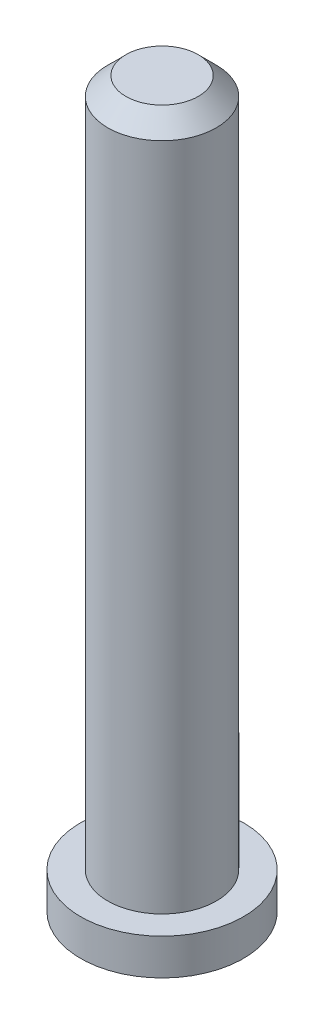
SolidWorks part; units mm, degrees
ref_plane "Спереди" through (0, 0, 0) normal (0, 0, 1) x (1, 0, 0)
ref_plane "Сверху" through (0, 0, 0) normal (0, 1, 0) x (1, 0, 0)
ref_plane "Справа" through (0, 0, 0) normal (1, 0, 0) x (0, 0, -1)
sketch "Эскиз1" plane through (0, 0, 0) normal (0, 1, 0) x (1, 0, 0)
  circle A0 centre (0, 0) radius 1.5
  dimension "D1" = 3
extrude "Вытянуть1" add sketch "Эскиз1" along normal blind 20
chamfer "Фаска1" distance 0.5 angle 45 1 edges at (0, 20, 1.5)
sketch "Эскиз2" plane through (0, 0, 0) normal (0, -1, 0) x (1, 0, 0)
  circle A0 centre (0, 0) radius 2.25
  dimension "D1" = 4.5
extrude "Вытянуть2" add sketch "Эскиз2" against normal blind 1
sketch "Эскиз3" plane through (0, 0, 0) normal (0, -1, 0) x (1, 0, 0)
  circle A0 centre (0, 0) radius 0.3
  dimension "D1" = 0.6
extrude "Вытянуть3" add sketch "Эскиз3" along normal blind 0.55
